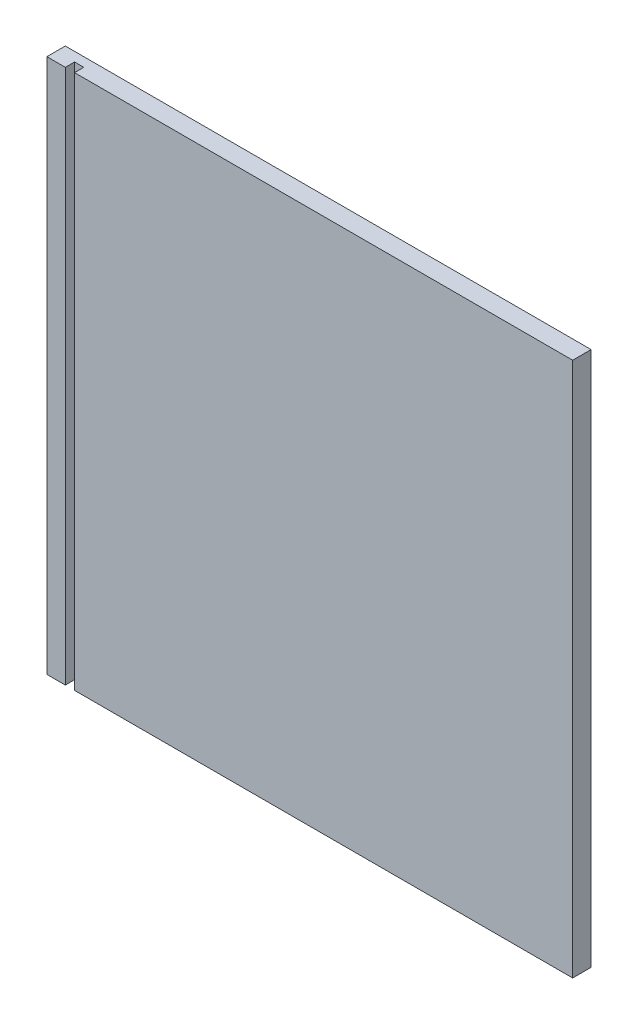
SolidWorks part; units mm, degrees
ref_plane "Plan de face" through (0, 0, 0) normal (0, 0, 1) x (1, 0, 0)
ref_plane "Plan de dessus" through (0, 0, 0) normal (0, 1, 0) x (1, 0, 0)
ref_plane "Plan de droite" through (0, 0, 0) normal (1, 0, 0) x (0, 0, -1)
sketch "Esquisse1" plane through (0, 0, 0) normal (0, 0, 1) x (1, 0, 0)
  line L1 (0, 0) -> (-285, 0)
  line L2 (0, 0) -> (0, 290)
  line L3 (0, 290) -> (-285, 290)
  line L4 (-285, 0) -> (-285, 290)
  dimension "D1" = 290
  dimension "D2" = 285
extrude "Boss.-Extru.1" add sketch "Esquisse1" along normal blind 10
sketch "Esquisse2" plane through (0, 0, 10) normal (0, 0, 1) x (1, 0, 0)
  line L0 (0, 290) -> (-285, 290) construction
  line L1 (-275, 290) -> (-270, 290)
  line L2 (-275, 290) -> (-275, 0)
  line L3 (-275, 0) -> (-270, 0)
  line L4 (-270, 290) -> (-270, 0)
  line L5 (-285, 0) -> (0, 0) construction
  line L6 (-285, 290) -> (-285, 0) construction
  dimension "D1" = 10
  dimension "D2" = 5
extrude "Enlèv. mat.-Extru.1" cut sketch "Esquisse2" against normal blind 5
